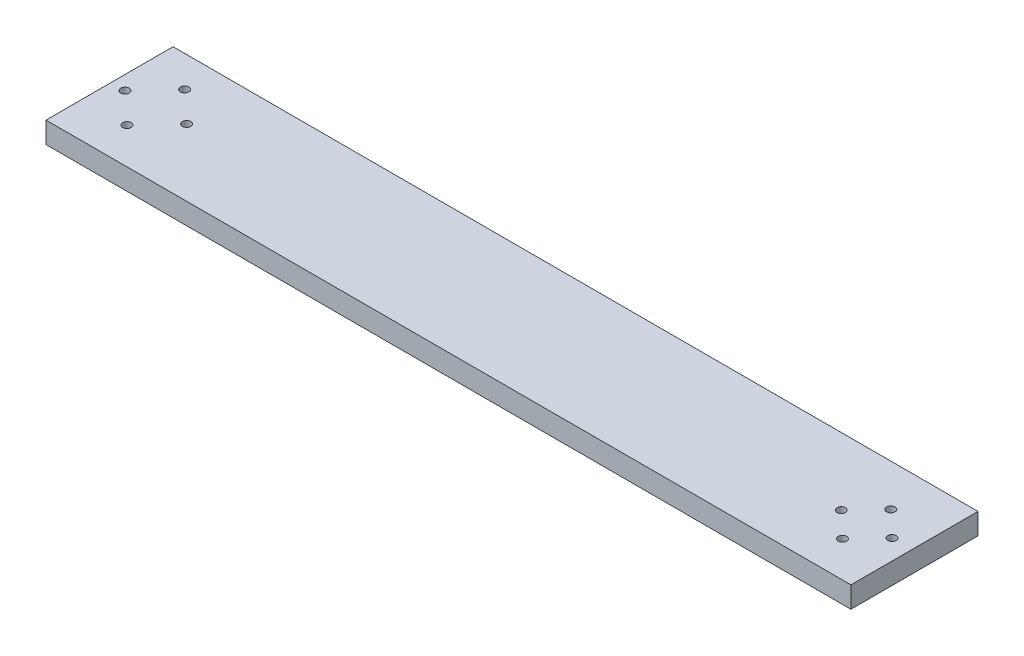
SolidWorks part; units mm, degrees
ref_plane "Front Plane" through (0, 0, 0) normal (0, 0, 1) x (1, 0, 0)
ref_plane "Top Plane" through (0, 0, 0) normal (0, 1, 0) x (1, 0, 0)
ref_plane "Right Plane" through (0, 0, 0) normal (1, 0, 0) x (0, 0, -1)
sketch "Sketch1" plane through (0, 0, 0) normal (0, 1, 0) x (1, 0, 0)
  line L0 (162.2477, 30) -> (162.2477, 48.3729) construction
  line L1 (0, 0) -> (190, 0)
  line L2 (0, 0) -> (0, 30)
  line L3 (0, 30) -> (190, 30)
  line L4 (190, 0) -> (190, 30)
  line L5 (162.2477, 48.3729) -> (162.2477, -19.8693) construction
  line L6 (22.3382, 45.738) -> (22.3382, -16.1805) construction
  line L7 (95, 30) -> (95, -4.8507) construction
  line L8 (95, -4.8507) -> (95.0595, -3.7968) construction
  dimension "D1" = 190
  dimension "D2" = 30
  dimension "D3" = 27.7523
extrude "Boss-Extrude6" add sketch "Sketch1" along normal blind 5
sketch "Sketch5" plane through (0, 5, 0) normal (0, 1, 0) x (1, 0, 0)
  circle A0 centre (185.2935, 14.4212) radius 1
  circle A1 centre (179.5934, 8.425) radius 1
  circle A2 centre (173.5973, 14.1251) radius 1
  circle A3 centre (179.2974, 20.1213) radius 1
  circle A4 centre (3.2853, 15.342) radius 1
  circle A5 centre (10.1019, 22.6257) radius 1
  circle A6 centre (17.3856, 15.809) radius 1
  circle A7 centre (10.569, 8.5254) radius 1
  point P11 (179.4454, 14.2732)
  point P20 (10.3354, 15.5755)
  dimension "D1" = 2
  dimension "D3" = 2
  dimension "D2" = 4
  dimension "D4" = 4
extrude "Cut-Extrude1" cut sketch "Sketch5" against normal blind 5
